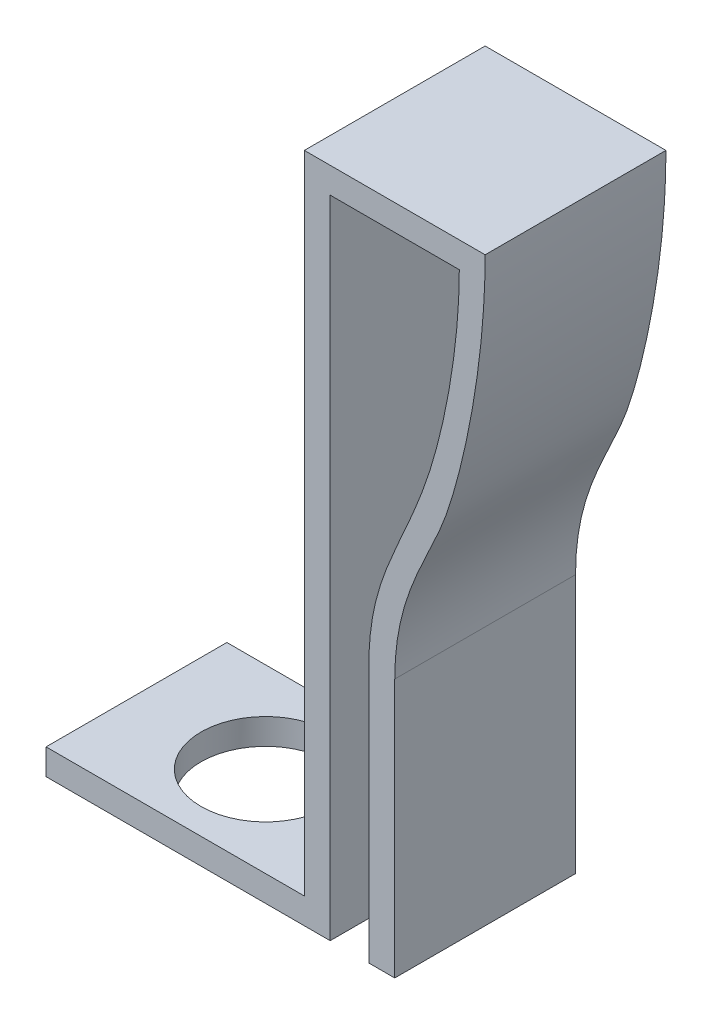
SolidWorks part; units mm, degrees
ref_plane "Front Plane" through (0, 0, 0) normal (0, 0, 1) x (1, 0, 0)
ref_plane "Top Plane" through (0, 0, 0) normal (0, 1, 0) x (1, 0, 0)
ref_plane "Right Plane" through (0, 0, 0) normal (1, 0, 0) x (0, 0, -1)
sketch "Sketch1" plane through (0, 0, 0) normal (0, 0, 1) x (1, 0, 0)
  line L0 (0, 0) -> (0, 25)
  line L1 (0, 25) -> (5, 25)
  line L2 (0, 0) -> (-1, 0)
  line L3 (-1, 26) -> (-1, 1)
  line L4 (1.5, 0) -> (1.5, 10)
  line L5 (1.5, 0) -> (2.5, 0)
  line L6 (2.5, 0) -> (2.5, 10.024)
  line L7 (1.5, 7.4753) -> (1.5, 12.5317) construction
  line L8 (-1, 26) -> (6, 26)
  line L9 (-1, 0) -> (-11, 0)
  line L10 (-11, 0) -> (-11, 1)
  line L11 (-11, 1) -> (-1, 1)
  spline S0 degree 3 poles (5, 25) (5, 22.5052) (3.7752, 15.544) (1.5, 13.1602) (1.5, 10) knots 0 0 0 0 0.413095 1 1 1 1
  spline S1 degree 3 poles (6, 26) (6, 22.3224) (5.0413, 17.9714) (3.7908, 14.6526) (2.5, 12.6969) (2.5, 10.024) knots 0 0 0 0 0.426694 0.526694 1 1 1 1
  dimension "D1" = 1
  dimension "D2" = 1
  dimension "D3" = 1.5
  dimension "D4" = 25
  dimension "D5" = 5
  dimension "D6" = 1
  dimension "D7" = 1
  dimension "D8" = 1
  dimension "D9" = 10
extrude "Boss-Extrude1" add sketch "Sketch1" along normal blind 7
sketch "Sketch5" plane through (0, 1, 0) normal (0, 1, 0) x (1, 0, 0)
  line L0 (-11, 0) -> (-1, -7) construction
  line L1 (-1, 0) -> (-11, -7) construction
  circle A0 centre (-6, -3.5) radius 2.5
extrude "Cut-Extrude1" cut sketch "Sketch5" against normal blind 7
